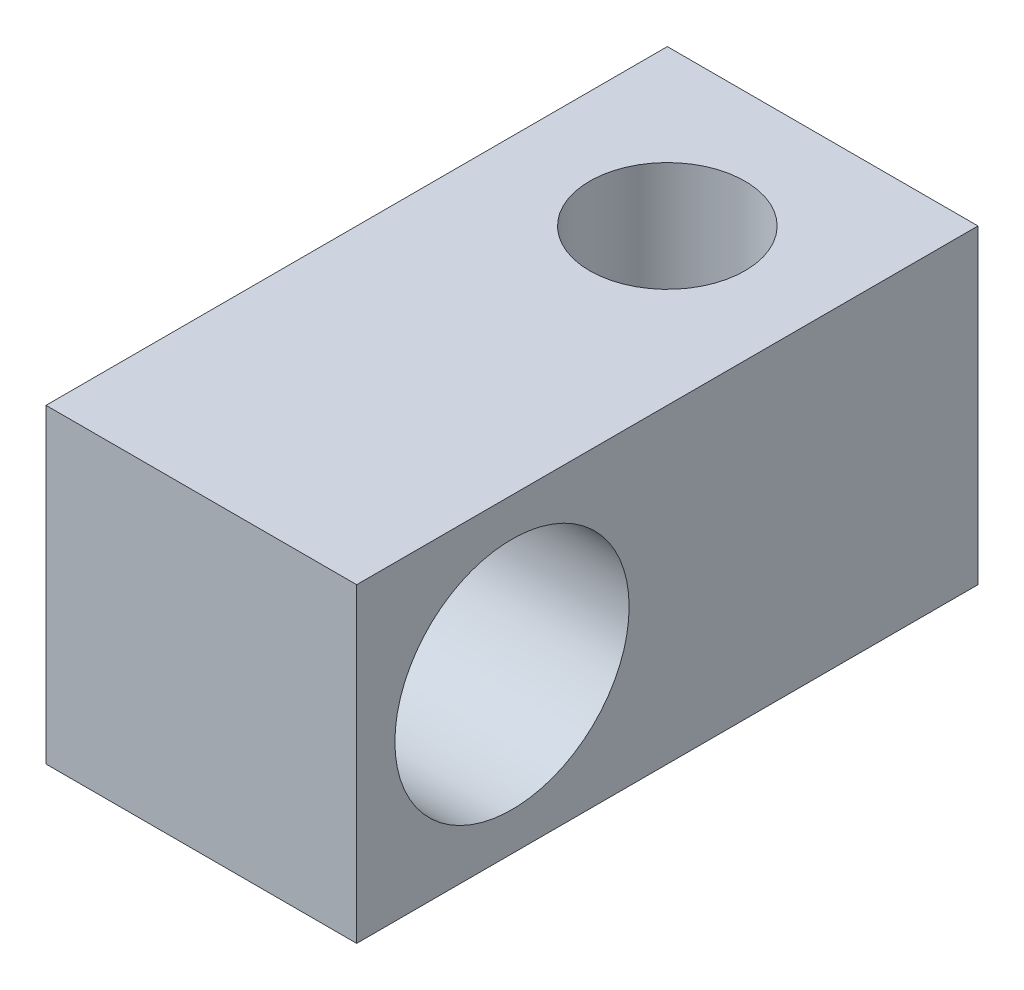
SolidWorks part; units mm, degrees
ref_plane "Płaszczyzna przednia" through (0, 0, 0) normal (0, 0, 1) x (1, 0, 0)
ref_plane "Płaszczyzna górna" through (0, 0, 0) normal (0, 1, 0) x (1, 0, 0)
ref_plane "Płaszczyzna prawa" through (0, 0, 0) normal (1, 0, 0) x (0, 0, -1)
sketch "Szkic1" plane through (0, 0, 0) normal (0, 0, 1) x (1, 0, 0)
  line L1 (0, 0) -> (50, 0)
  line L2 (0, 0) -> (0, 50)
  line L3 (0, 50) -> (50, 50)
  line L4 (50, 0) -> (50, 50)
  dimension "D1" = 50
  dimension "D2" = 50
extrude "Dodanie-wyciągnięcie1" add sketch "Szkic1" along normal blind 100
sketch "Szkic2" plane through (0, 50, 0) normal (0, 1, 0) x (1, 0, 0)
  line L0 (50, 0) -> (0, 0) construction
  line L1 (0, -100) -> (0, 0) construction
  circle A0 centre (25, -25) radius 12.5
  dimension "D1" = 25
  dimension "D2" = 25
  dimension "D3" = 25
extrude "Wytnij-wyciągnięcie1" cut sketch "Szkic2" against normal up to next
sketch "Szkic3" plane through (0, 0, 0) normal (-1, 0, 0) x (0, 0, 1)
  line L0 (100, 50) -> (100, 0) construction
  line L1 (100, 50) -> (0, 50) construction
  circle A0 centre (75, 25) radius 18.85
  dimension "D3" = 37.7
  dimension "D1" = 25
  dimension "D2" = 25
extrude "Wytnij-wyciągnięcie2" cut sketch "Szkic3" against normal up to next
